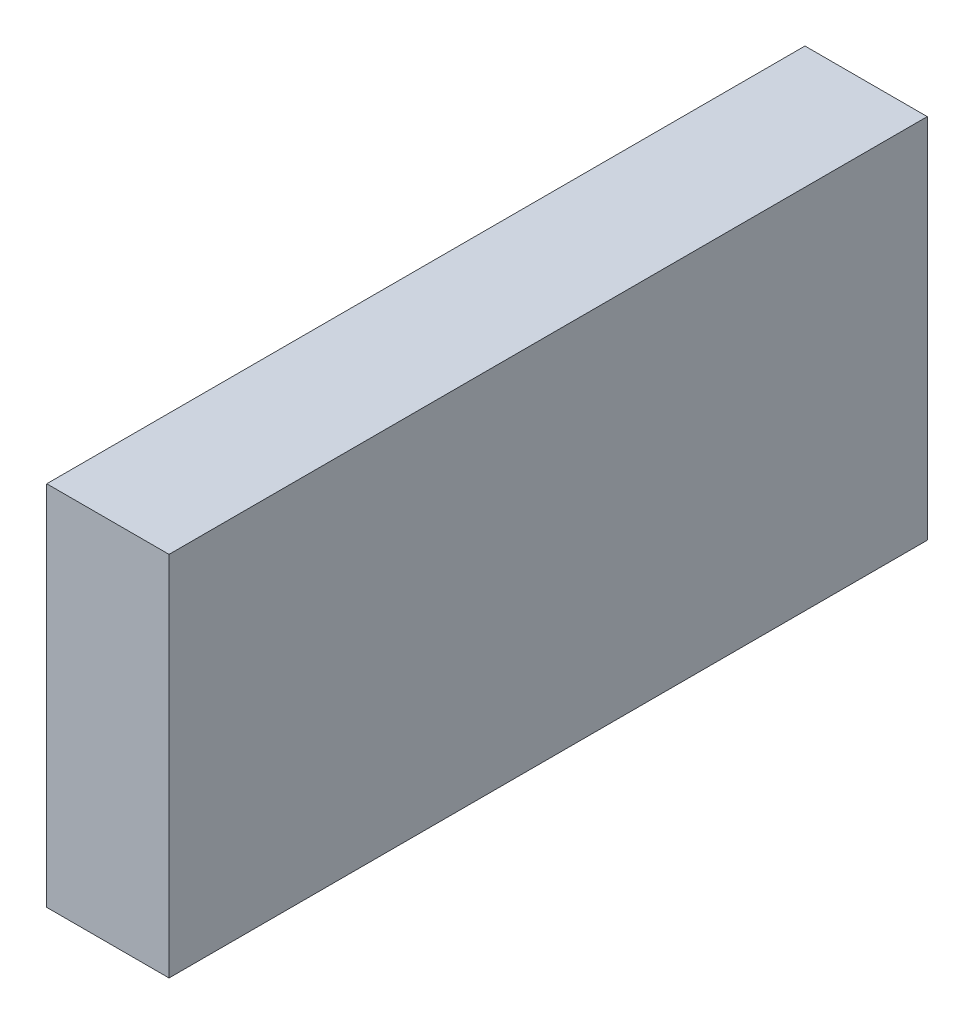
SolidWorks part; units mm, degrees
ref_plane "Front Plane" through (0, 0, 0) normal (0, 0, 1) x (1, 0, 0)
ref_plane "Top Plane" through (0, 0, 0) normal (0, 1, 0) x (1, 0, 0)
ref_plane "Right Plane" through (0, 0, 0) normal (1, 0, 0) x (0, 0, -1)
sketch "Sketch1" plane through (0, 0, 0) normal (0, 0, 1) x (1, 0, 0)
  line L1 (-10, -30) -> (10, -30)
  line L2 (-10, -30) -> (-10, 30)
  line L3 (-10, 30) -> (10, 30)
  line L4 (10, -30) -> (10, 30)
  line L5 (-10, -30) -> (10, 30) construction
  line L6 (-10, 30) -> (10, -30) construction
  point P0 (0, 0)
  dimension "D1" = 60
  dimension "D2" = 20
extrude "Boss-Extrude1" add sketch "Sketch1" along normal mid plane 124
